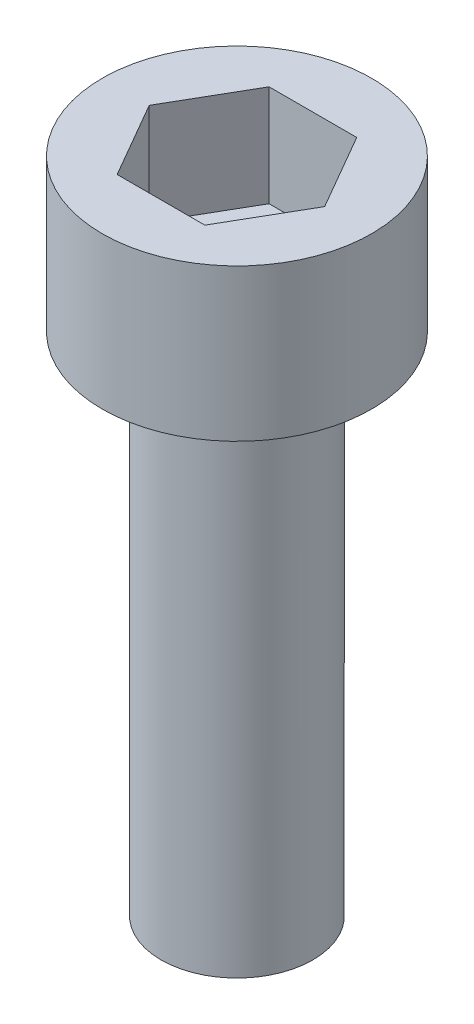
SolidWorks part; units mm, degrees
ref_plane "Front Plane" through (0, 0, 0) normal (0, 0, 1) x (1, 0, 0)
ref_plane "Top Plane" through (0, 0, 0) normal (0, 1, 0) x (1, 0, 0)
ref_plane "Right Plane" through (0, 0, 0) normal (1, 0, 0) x (0, 0, -1)
sketch "Sketch1" plane through (0, 0, 0) normal (0, 1, 0) x (1, 0, 0)
  circle A0 centre (0, 0) radius 2.66
  dimension "D1" = 5.32
extrude "Boss-Extrude1" add sketch "Sketch1" along normal blind 3
sketch "Sketch2" plane through (0, 3, 0) normal (0, 1, 0) x (1, 0, 0)
  line L1 (1.7321, 0) -> (0.866, 1.5)
  line L2 (0.866, 1.5) -> (-0.866, 1.5)
  line L3 (-0.866, 1.5) -> (-1.7321, 0)
  line L4 (-1.7321, 0) -> (-0.866, -1.5)
  line L5 (-0.866, -1.5) -> (0.866, -1.5)
  line L6 (0.866, -1.5) -> (1.7321, 0)
  circle A0 centre (0, 0) radius 1.5 construction
  dimension "D1" = 3
extrude "Cut-Extrude1" cut sketch "Sketch2" against normal blind 2
sketch "Sketch3" plane through (0, 0, 0) normal (0, -1, 0) x (1, 0, 0)
  circle A0 centre (0, 0) radius 1.5
  dimension "D1" = 3
extrude "Boss-Extrude2" add sketch "Sketch3" along normal blind 10
